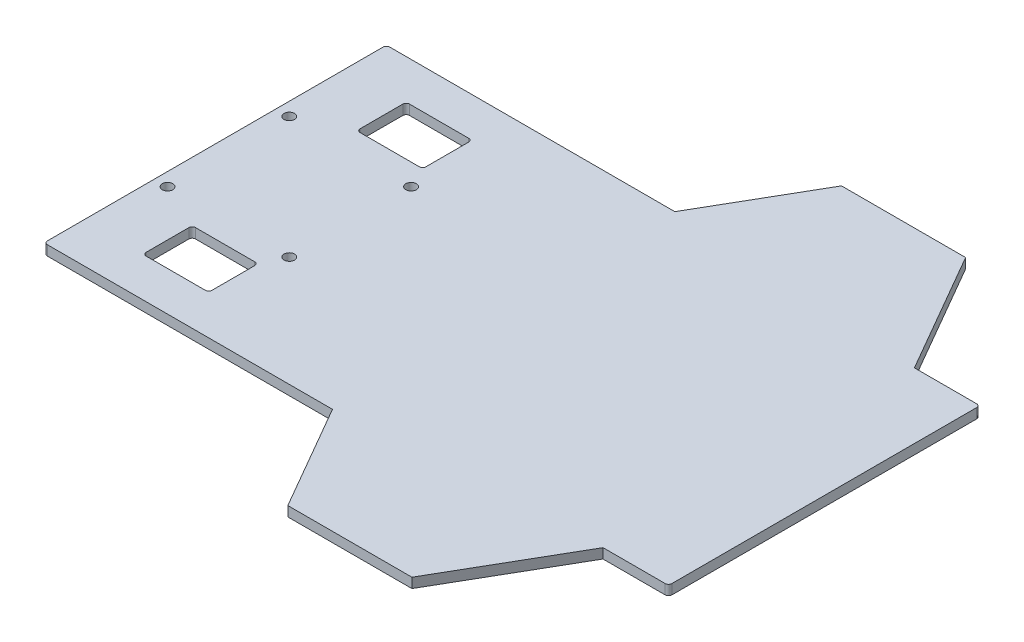
SolidWorks part; units mm, degrees
material "Acrylic (Medium-high impact)"
ref_plane "Front Plane" through (0, 0, 0) normal (0, 0, 1) x (1, 0, 0)
ref_plane "Top Plane" through (0, 0, 0) normal (0, 1, 0) x (1, 0, 0)
ref_plane "Right Plane" through (0, 0, 0) normal (1, 0, 0) x (0, 0, -1)
sketch "Sketch1" plane through (0, 0, 0) normal (0, 1, 0) x (1, 0, 0)
  line L0 (0, 52) -> (0, -52)
  line L12 (0, 52) -> (87.6171, 52)
  line L13 (87.6171, 52) -> (106.15, 84.1)
  line L14 (106.15, 84.1) -> (143.85, 84.1)
  line L15 (143.85, 84.1) -> (165.0965, 47.3)
  line L16 (165.0965, 47.3) -> (185, 47.3)
  line L17 (185, 47.3) -> (185, -47.3)
  line L18 (185, -47.3) -> (165.0965, -47.3)
  line L19 (165.0965, -47.3) -> (143.85, -84.1)
  line L20 (143.85, -84.1) -> (106.15, -84.1)
  line L21 (106.15, -84.1) -> (87.6171, -52)
  line L22 (87.6171, -52) -> (0, -52)
  line L23 (125, 84.1) -> (125, -84.1) construction
  point P12 (125, 0)
  point P15 (0, 0)
  point P23 (185, 0)
  dimension "D1" = 104
  dimension "D2" = 37.7
  dimension "D3" = 32.1
  dimension "D4" = 120
  dimension "D5" = 143.85
  dimension "D6" = 185
  dimension "D7" = 94.6
extrude "Boss-Extrude1" add sketch "Sketch1" along normal blind 3
fillet "Fillet1" radius 1 4 edges at (0, 1.5, 52) (0, 1.5, -52) (185, 1.5, -47.3) (185, 1.5, 47.3)
sketch "Sketch2" plane through (0, 3, 0) normal (0, 1, 0) x (1, 0, 0)
  line L0 (0, 51) -> (0, -51) construction
  line L1 (4, 18.5) -> (41, 18.5) construction
  line L2 (4, 18.5) -> (4, -18.5) construction
  line L3 (4, -18.5) -> (41, -18.5) construction
  line L4 (41, 18.5) -> (41, -18.5) construction
  circle A0 centre (4, 18.5) radius 1.6
  circle A1 centre (41, 18.5) radius 1.6
  circle A2 centre (4, -18.5) radius 1.6
  circle A3 centre (41, -18.5) radius 1.6
  point P4 (4, 0)
  dimension "D3" = 3.2
  dimension "D4" = 4
  dimension "D1" = 37
  dimension "D2" = 37
extrude "Motor Driver Holes" cut sketch "Sketch2" against normal through all
sketch "Sketch3" plane through (0, 3, 0) normal (0, 1, 0) x (1, 0, 0)
  line L1 (38, 25) -> (18, 25)
  line L2 (38, 25) -> (38, 40)
  line L3 (38, 40) -> (18, 40)
  line L4 (18, 25) -> (18, 40)
  circle A0 centre (41, 18.5) radius 1.6 construction
  dimension "D1" = 25
  dimension "D2" = 20
  dimension "D3" = 3
  dimension "D4" = 15
extrude "Motor Driver Routing Pocket" cut sketch "Sketch3" against normal through all
fillet "Motor Driver Routing Pocket Fillets" radius 1 4 edges at (38, 1.5, -25) (38, 1.5, -40) (18, 1.5, -25) (18, 1.5, -40)
mirror "Mirror1" about plane through (0, 0, 0) normal (0, 0, 1) of "Motor Driver Routing Pocket", "Motor Driver Routing Pocket Fillets"
